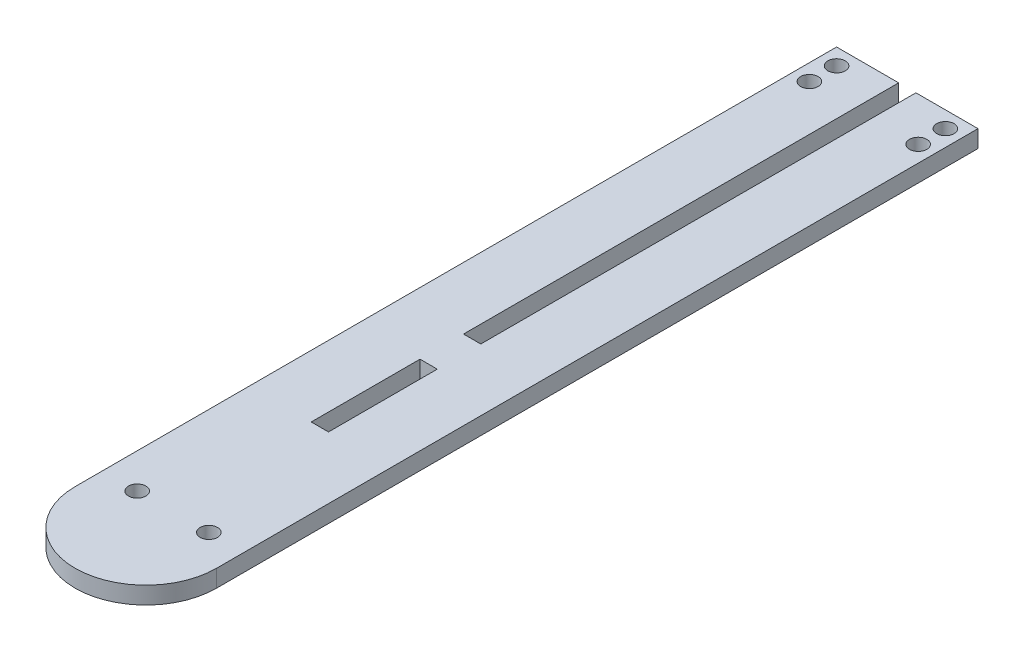
SolidWorks part; units mm, degrees
ref_plane "Front Plane" through (0, 0, 0) normal (0, 0, 1) x (1, 0, 0)
ref_plane "Top Plane" through (0, 0, 0) normal (0, 1, 0) x (1, 0, 0)
ref_plane "Right Plane" through (0, 0, 0) normal (1, 0, 0) x (0, 0, -1)
sketch "Sketch1" plane through (0, 0, 0) normal (0, 1, 0) x (1, 0, 0)
  line L1 (-14.5875, 0) -> (-14.5875, -140)
  line L2 (11.4125, 0) -> (11.4125, -140)
  line L3 (-14.5875, 0) -> (-3.175, 0)
  line L5 (-3.175, 0) -> (-3.175, -80)
  line L6 (-3.175, -80) -> (0, -80)
  line L7 (0, 0) -> (0, -80)
  line L8 (11.4125, 0) -> (0, 0)
  line L9 (0, -68) -> (-3.175, -68) construction
  line L10 (-3.175, -88) -> (0, -88)
  line L11 (-3.175, -88) -> (-3.175, -108)
  line L12 (-3.175, -108) -> (0, -108)
  line L13 (0, -88) -> (0, -108)
  arc A0 (-14.5875, -140) -> (11.4125, -140) centre (-1.5875, -140) ccw
  point P6 (-8.8812, 0)
  dimension "D1" = 26
  dimension "D2" = 140
  dimension "D3" = 3.175
  dimension "D4" = 80
  dimension "D5" = 20
  dimension "D6" = 20
  dimension "D7" = 12
extrude "Boss-Extrude1" add sketch "Sketch1" along normal blind 3.175
sketch "Sketch2" plane through (0, 3.175, 0) normal (0, 1, 0) x (1, 0, 0)
  circle A0 centre (5, -135) radius 1.6 construction
  circle A1 centre (-8.175, -135) radius 1.6 construction
  circle A2 centre (5, -135) radius 1.6
  circle A3 centre (-8.175, -135) radius 1.6
extrude "Cut-Extrude1" cut sketch "Sketch2" against normal through all both and the other way through all
sketch "Sketch3" plane through (0, 3.175, 0) normal (0, 1, 0) x (1, 0, 0)
  circle A0 centre (-11.5875, -8) radius 1.6 construction
  circle A1 centre (-11.5875, -3) radius 1.6 construction
  circle A2 centre (8.4125, -8) radius 1.6 construction
  circle A3 centre (8.4125, -3) radius 1.6 construction
  circle A4 centre (-11.5875, -8) radius 1.6
  circle A5 centre (-11.5875, -3) radius 1.6
  circle A6 centre (8.4125, -8) radius 1.6
  circle A7 centre (8.4125, -3) radius 1.6
extrude "Cut-Extrude2" cut sketch "Sketch3" against normal through all both and the other way through all
